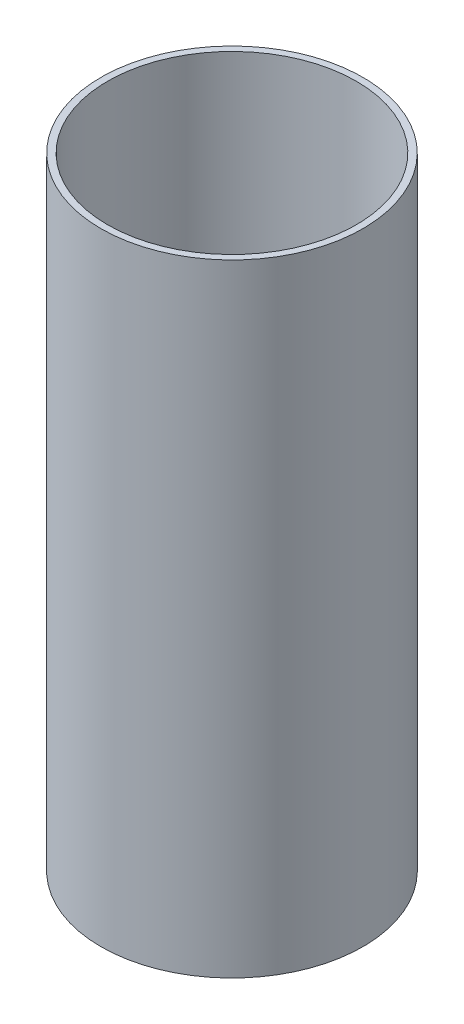
SolidWorks part; units mm, degrees
material "PVC Rigid"
ref_plane "Front Plane" through (0, 0, 0) normal (0, 0, 1) x (1, 0, 0)
ref_plane "Top Plane" through (0, 0, 0) normal (0, 1, 0) x (1, 0, 0)
ref_plane "Right Plane" through (0, 0, 0) normal (1, 0, 0) x (0, 0, -1)
sketch "Sketch1" plane through (0, 0, 0) normal (0, 1, 0) x (1, 0, 0)
  circle A0 centre (0, 0) radius 93.6625
  circle A1 centre (0, 0) radius 88.9
  dimension "D1" = 187.325
  dimension "D2" = 177.8
extrude "Boss-Extrude1" add sketch "Sketch1" along normal mid plane 444.5
ref_plane "Plane1" through (-93.6625, 0, 0) normal (-1, 0, 0) x (0, 0, 1)
sketch "Sketch3" plane through (-93.6625, 0, 0) normal (-1, 0, 0) x (0, 0, 1)
  line L0 (0, -103.0288) -> (0, 103.0288) construction
  line L1 (-88.9, -222.25) -> (88.9, -222.25) construction
  circle A0 centre (0, -215.9) radius 1.4351
  dimension "D1" = 2.8702
  dimension "D2" = 6.35
extrude "Cut-Extrude1" [suppressed] cut sketch "Sketch3" against normal blind 21.59
pattern_circular "CirPattern1" [suppressed] count 12 over 360
sketch "Sketch4" plane through (-93.6625, 0, 0) normal (-1, 0, 0) x (0, 0, 1)
  line L0 (0, -103.0288) -> (0, 103.0288) construction
  line L1 (93.6625, 222.25) -> (-93.6625, 222.25) construction
  circle A0 centre (0, 215.9) radius 1.4351
  dimension "D1" = 2.8702
  dimension "D2" = 6.35
extrude "Cut-Extrude2" [suppressed] cut sketch "Sketch4" against normal blind 34.798
pattern_circular "CirPattern2" [suppressed] count 3 over 360
sketch "Sketch9" [suppressed] plane through (-93.6625, 0, 0) normal (-1, 0, 0) x (0, 0, 1)
  line L0 (0, -103.0288) -> (0, 103.0288) construction
  circle A0 centre (0, 130.048) radius 1.4351
  circle A1 centre (0, 215.9) radius 1.4351 construction
  dimension "D1" = 85.852
  dimension "D2" = 2.8702
extrude "Cut-Extrude4" [suppressed] cut sketch "Sketch9" against normal blind 15.24
pattern_circular "CirPattern4" [suppressed] count 12 over 360
sketch "Sketch7" [suppressed] plane through (-93.6625, 0, 0) normal (-1, 0, 0) x (0, 0, 1)
  line L0 (0, -103.0288) -> (0, 103.0288) construction
  circle A0 centre (0, 6.35) radius 1.4351
  circle A1 centre (0, -98.552) radius 1.4351
  circle A4 centre (0, 130.048) radius 1.4351 construction
  circle A5 centre (0, -215.9) radius 1.4351 construction
  dimension "D1" = 123.698
  dimension "D2" = 117.348
  dimension "D3" = 2.8702
  dimension "D4" = 2.8702
extrude "Cut-Extrude3" [suppressed] cut sketch "Sketch7" against normal blind 15.24
pattern_circular "CirPattern3" [suppressed] count 3 over 360
sketch "Sketch10" [suppressed] plane through (-93.6625, 0, 0) normal (-1, 0, 0) x (0, 0, 1)
  line L0 (0, -103.0288) -> (0, 103.0288) construction
  circle A0 centre (0, 205.74) radius 1.4351
  circle A1 centre (0, 215.9) radius 1.4351 construction
  dimension "D1" = 10.16
  dimension "D2" = 2.8702
extrude "Cut-Extrude5" [suppressed] cut sketch "Sketch10" against normal blind 21.082
pattern_circular "CirPattern5" [suppressed] count 12 over 360
